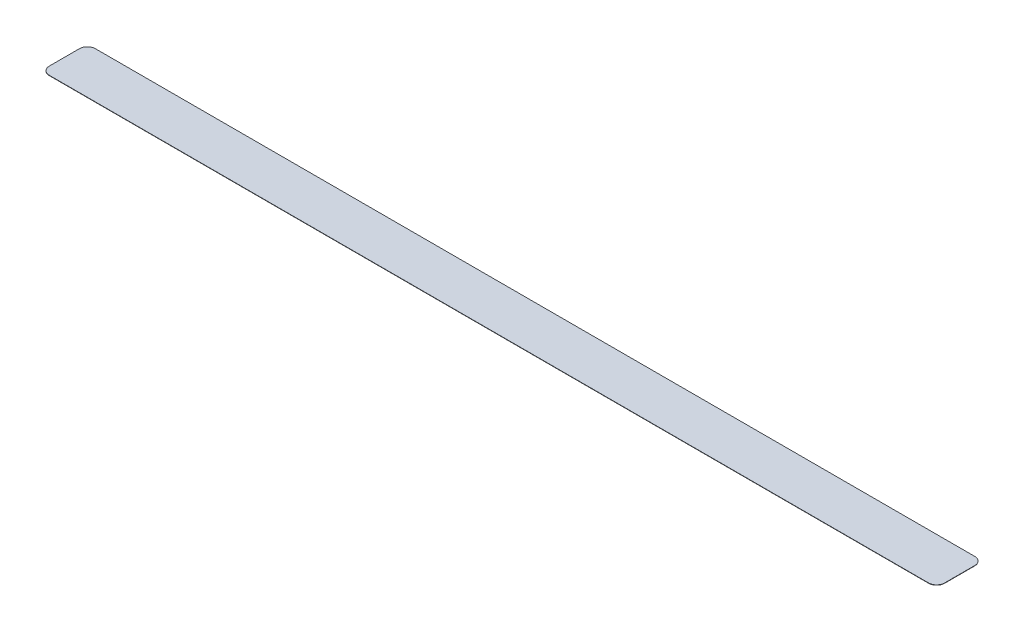
SolidWorks part; units mm, degrees
ref_plane "Ebene vorne" through (0, 0, 0) normal (0, 0, 1) x (1, 0, 0)
ref_plane "Ebene oben" through (0, 0, 0) normal (0, 1, 0) x (1, 0, 0)
ref_plane "Ebene rechts" through (0, 0, 0) normal (1, 0, 0) x (0, 0, -1)
sketch "Skizze1" plane through (0, 0, 0) normal (0, 1, 0) x (1, 0, 0)
  line L0 (-138.375, 7.25) -> (138.375, 7.25)
  line L1 (-140.875, 4.75) -> (-140.875, -4.75)
  line L2 (-138.375, -7.25) -> (138.375, -7.25)
  line L3 (140.875, 4.75) -> (140.875, -4.75)
  arc A0 (-138.375, 7.25) -> (-140.875, 4.75) centre (-138.375, 4.75) ccw
  arc A1 (-140.875, -4.75) -> (-138.375, -7.25) centre (-138.375, -4.75) ccw
  arc A2 (138.375, 7.25) -> (140.875, 4.75) centre (138.375, 4.75) cw
  arc A3 (138.375, -7.25) -> (140.875, -4.75) centre (138.375, -4.75) ccw
  point P12 (0, 0)
  dimension "D1" = 2.5
extrude "Aufsatz-Linear austragen1" add sketch "Skizze1" along normal blind 0.1
